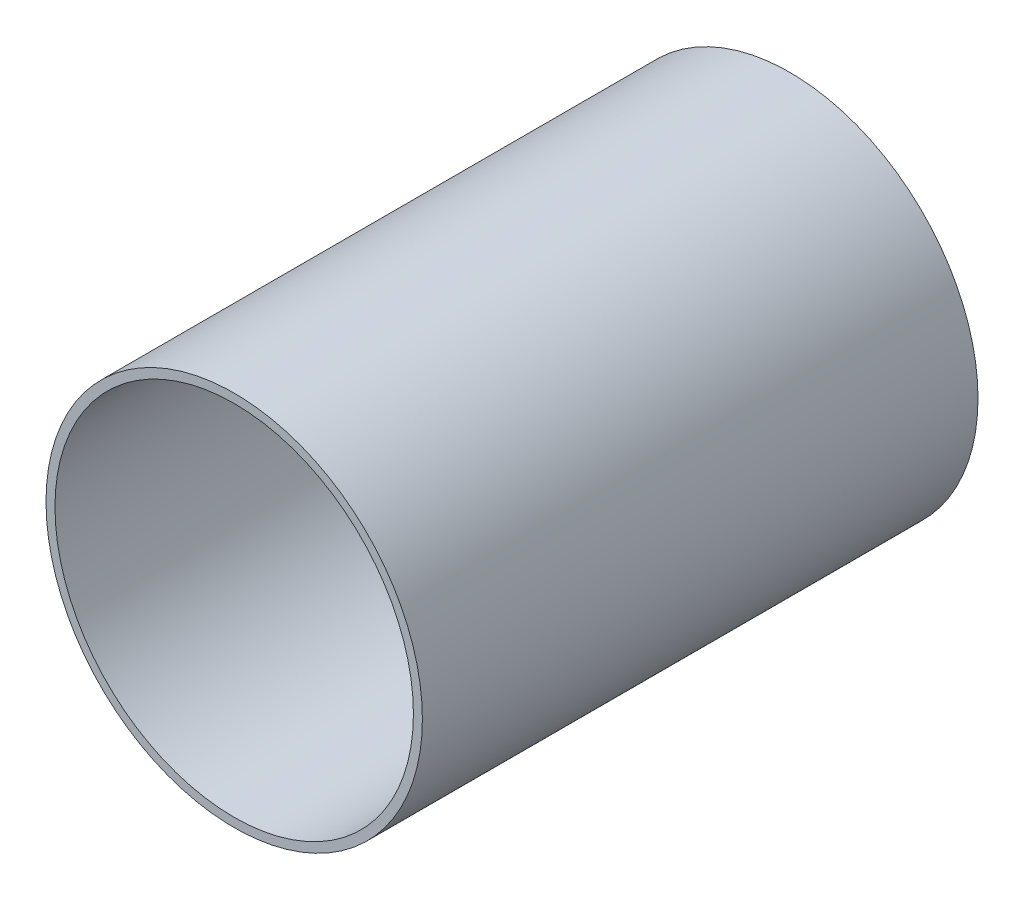
SolidWorks part; units mm, degrees
ref_plane "Front Plane" through (0, 0, 0) normal (0, 0, 1) x (1, 0, 0)
ref_plane "Top Plane" through (0, 0, 0) normal (0, 1, 0) x (1, 0, 0)
ref_plane "Right Plane" through (0, 0, 0) normal (1, 0, 0) x (0, 0, -1)
sketch "Sketch1" plane through (0, 0, 0) normal (0, 0, 1) x (1, 0, 0)
  circle A0 centre (0, 0) radius 5
  circle A1 centre (0, 0) radius 5.25
  dimension "D1" = 10
  dimension "D2" = 0.25
extrude "Boss-Extrude1" add sketch "Sketch1" along normal blind 15.5
